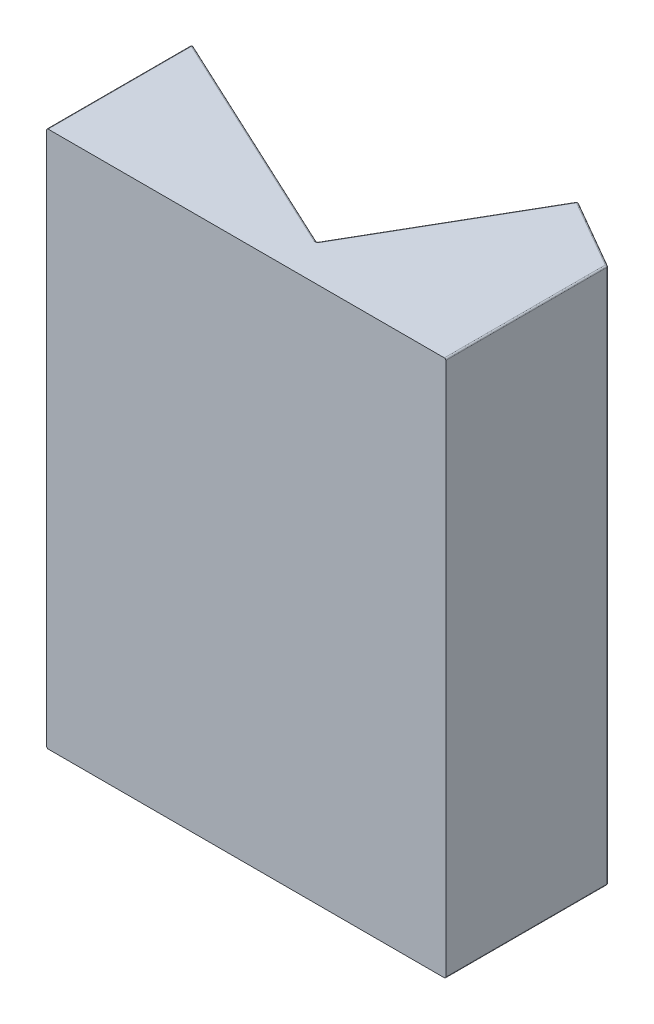
SolidWorks part; units mm, degrees
ref_plane "Front Plane" through (0, 0, 0) normal (0, 0, 1) x (1, 0, 0)
ref_plane "Top Plane" through (0, 0, 0) normal (0, 1, 0) x (1, 0, 0)
ref_plane "Right Plane" through (0, 0, 0) normal (1, 0, 0) x (0, 0, -1)
sketch "Sketch1" plane through (0, 0, 0) normal (0, 1, 0) x (1, 0, 0)
  line L0 (0, 0) -> (54.2759, 0)
  line L1 (31.7208, 5) -> (0, 19.7916)
  line L2 (0, 19.7916) -> (0, 0)
  line L3 (31.7208, 5) -> (44.7208, 27.5167)
  line L4 (44.7208, 27.5167) -> (54.2759, 22)
  line L5 (54.2759, 22) -> (54.2759, 0)
  line L6 (31.7208, 5) -> (31.7208, 0)
  dimension "D1" = 25
  dimension "D2" = 26
  dimension "D3" = 35
  dimension "D4" = 5
  dimension "D5" = 22
  dimension "D6" = 95
extrude "Boss-Extrude1" add sketch "Sketch1" along normal blind 73 contours L3 L4 L5 L0 L2 L1
fillet "Fillet1" radius 0.2 14 edges at (15.8604, 0, -12.3958) (38.2208, 0, -16.2583) (38.2208, 73, -16.2583) (15.8604, 73, -12.3958) (0, 36.5, -19.7916) (0, 73, -9.8958) (0, 0, -9.8958) (31.7208, 36.5, -5) (54.2759, 0, -11) (49.4983, 0, -24.7583) (49.4983, 73, -24.7583) (54.2759, 73, -11) (54.2759, 36.5, -22) (44.7208, 36.5, -27.5167)
